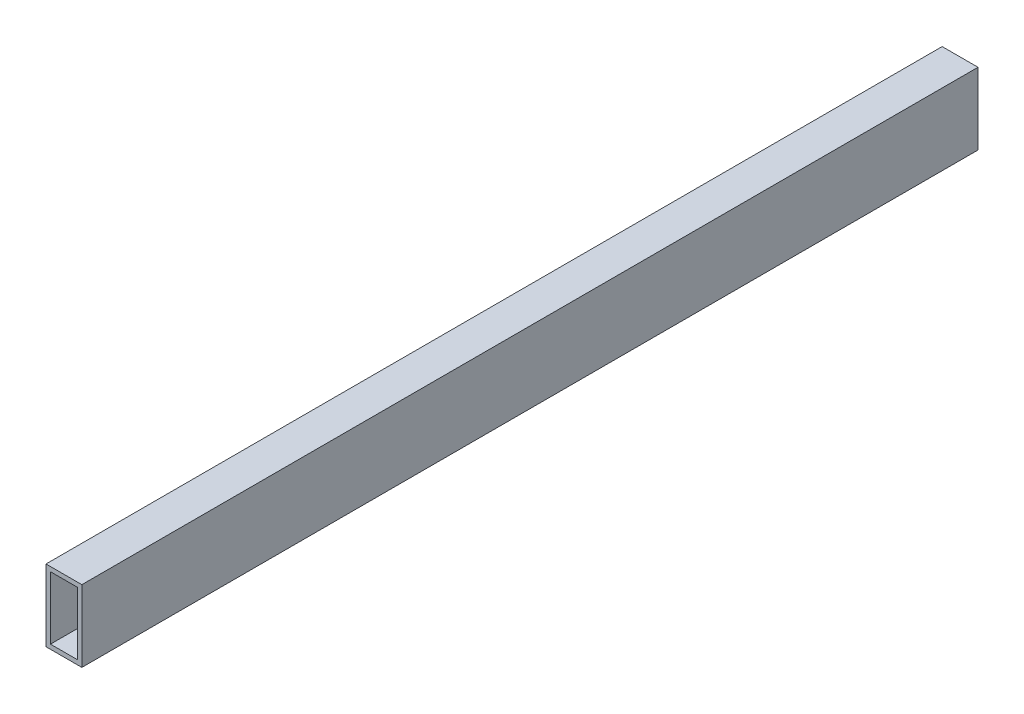
SolidWorks part; units mm, degrees
ref_plane "Front Plane" through (0, 0, 0) normal (0, 0, 1) x (1, 0, 0)
ref_plane "Top Plane" through (0, 0, 0) normal (0, 1, 0) x (1, 0, 0)
ref_plane "Right Plane" through (0, 0, 0) normal (1, 0, 0) x (0, 0, -1)
sketch "Sketch1" plane through (0, 0, 0) normal (0, 0, 1) x (1, 0, 0)
  line L1 (0, 0) -> (25.4, 0)
  line L2 (0, 0) -> (0, 50.8)
  line L3 (0, 50.8) -> (25.4, 50.8)
  line L4 (25.4, 0) -> (25.4, 50.8)
  line L5 (3.175, 3.175) -> (22.225, 3.175)
  line L6 (3.175, 3.175) -> (3.175, 47.625)
  line L7 (3.175, 47.625) -> (22.225, 47.625)
  line L8 (22.225, 3.175) -> (22.225, 47.625)
  dimension "D1" = 3.175
  dimension "D2" = 50.8
  dimension "D3" = 25.4
  dimension "D4" = 3.175
  dimension "D5" = 3.175
  dimension "D6" = 3.175
extrude "Boss-Extrude1" add sketch "Sketch1" along normal blind 635
